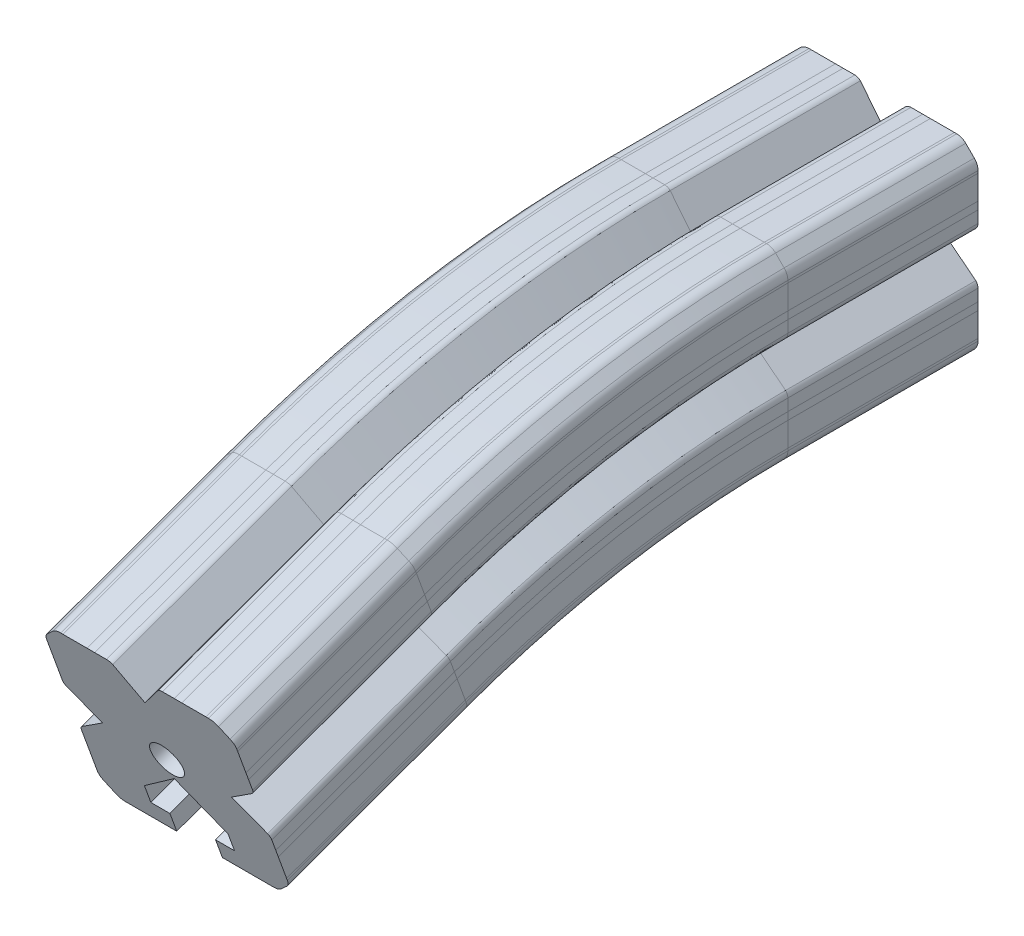
SolidWorks part; units mm, degrees
material "PET"
ref_plane "Front Plane" through (0, 0, 0) normal (0, 0, 1) x (1, 0, 0)
ref_plane "Top Plane" through (0, 0, 0) normal (0, 1, 0) x (1, 0, 0)
ref_plane "Right Plane" through (0, 0, 0) normal (1, 0, 0) x (0, 0, -1)
ref_plane "Plane1" through (0, 0, -304.8) normal (0, 0, -1) x (-1, 0, 0)
sketch "Sketch1" plane through (0, 0, -304.8) normal (0, 0, -1) x (-1, 0, 0)
  line L0 (14.3277, 19.117) -> (9.4982, 19.117)
  line L1 (7.9742, 19.117) -> (5.6176, 19.117)
  line L2 (4.064, 17.5634) -> (4.064, 16.6067) construction
  line L10 (-4.064, 16.6067) -> (-4.064, 17.5634) construction
  line L11 (-5.6176, 19.117) -> (-7.9742, 19.117)
  line L12 (-9.4982, 19.117) -> (-14.3277, 19.117)
  line L13 (-19.05, 14.3948) -> (-19.05, 9.5631)
  line L14 (-19.05, 8.0434) -> (-19.05, 5.6847)
  line L15 (-17.4964, 4.131) -> (-16.5396, 4.131) construction
  line L23 (-16.5396, -3.997) -> (-17.4964, -3.997) construction
  line L24 (-19.05, -5.5506) -> (-19.05, -7.9093)
  line L25 (-19.05, -9.429) -> (-19.05, -14.2607)
  line L26 (-14.3277, -18.983) -> (-9.4961, -18.983)
  line L27 (-7.9763, -18.983) -> (-5.6176, -18.983)
  line L37 (5.6176, -18.983) -> (7.9763, -18.983)
  line L38 (9.4961, -18.983) -> (14.3277, -18.983)
  line L39 (19.05, -14.2607) -> (19.05, -9.429)
  line L40 (19.05, -7.9093) -> (19.05, -5.5506)
  line L41 (17.4964, -3.997) -> (16.5396, -3.997) construction
  line L49 (16.5396, 4.131) -> (17.4964, 4.131) construction
  line L50 (19.05, 5.6847) -> (19.05, 8.0434)
  line L51 (19.05, 9.5631) -> (19.05, 14.3948)
  line L52 (19.05, 5.6847) -> (17.4964, 5.6847) construction
  line L53 (17.4964, 5.6847) -> (17.4964, 4.131) construction
  line L54 (17.4964, 5.6847) -> (18.5065, 4.5043) construction
  line L55 (16.5396, 4.131) -> (12.8784, 0.067) construction
  line L56 (4.064, 16.6067) -> (4.064, 12.9818) construction
  line L57 (4.064, 12.9818) -> (-4.064, 12.9818) construction
  line L58 (-4.064, 12.9818) -> (-4.064, 16.6067) construction
  line L62 (-5.6176, -18.983) -> (5.6176, -18.983)
  line L66 (12.8784, 0.067) -> (16.5396, -3.997) construction
  line L67 (-16.5396, 4.131) -> (-12.8784, 0.067) construction
  line L68 (-12.8784, 0.067) -> (-16.5396, -3.997) construction
  line L69 (-15.8475, 19.117) -> (-14.3277, 19.117)
  line L70 (-9.4982, 19.117) -> (-7.9742, 19.117)
  line L71 (7.9742, 19.117) -> (9.4982, 19.117)
  line L72 (14.3277, 19.117) -> (15.8475, 19.117)
  line L73 (19.05, 15.9145) -> (19.05, 14.3948)
  line L74 (19.05, 9.5631) -> (19.05, 8.0434)
  line L75 (19.05, -7.9093) -> (19.05, -9.429)
  line L76 (19.05, -14.2607) -> (19.05, -15.7805)
  line L77 (15.8475, -18.983) -> (14.3277, -18.983)
  line L78 (9.4961, -18.983) -> (7.9763, -18.983)
  line L79 (-7.9763, -18.983) -> (-9.4961, -18.983)
  line L80 (-14.3277, -18.983) -> (-15.8475, -18.983)
  line L81 (-19.05, -15.7805) -> (-19.05, -14.2607)
  line L82 (-19.05, -9.429) -> (-19.05, -7.9093)
  line L83 (-19.05, 8.0434) -> (-19.05, 9.5631)
  line L84 (-19.05, 14.3948) -> (-19.05, 15.9145)
  line L85 (-15.8475, -18.983) -> (-19.05, -15.7805)
  line L86 (15.8475, -18.983) -> (19.05, -15.7805)
  line L87 (0, 12.9818) -> (4.519, 18.662)
  line L88 (-4.519, 18.662) -> (0, 12.9818)
  line L89 (18.5065, 4.5043) -> (12.8784, 0.067)
  line L90 (12.8784, 0.067) -> (18.595, -4.452)
  line L91 (-18.595, 4.5861) -> (-12.8784, 0.067)
  line L92 (-18.595, -4.452) -> (-12.8784, 0.067)
  line L93 (-19.05, 15.9145) -> (-15.8475, 19.117)
  line L94 (15.8475, 19.117) -> (19.05, 15.9145)
  arc A2 (5.6176, 19.117) -> (4.064, 17.5634) centre (5.6176, 17.5634) ccw construction
  arc A11 (-4.064, 17.5634) -> (-5.6176, 19.117) centre (-5.6176, 17.5634) ccw construction
  arc A14 (-15.8475, 19.117) -> (-19.05, 15.9145) centre (-15.8751, 15.9422) ccw construction
  arc A17 (-19.05, 5.6847) -> (-17.4964, 4.131) centre (-17.4964, 5.6847) ccw construction
  arc A26 (-17.4964, -3.997) -> (-19.05, -5.5506) centre (-17.4964, -5.5506) ccw construction
  arc A29 (-19.05, -15.7805) -> (-15.8475, -18.983) centre (-15.8751, -15.8081) ccw construction
  arc A44 (15.8475, -18.983) -> (19.05, -15.7805) centre (15.8751, -15.8081) ccw construction
  arc A47 (19.05, -5.5506) -> (17.4964, -3.997) centre (17.4964, -5.5506) ccw construction
  arc A56 (17.4964, 4.131) -> (19.05, 5.6847) centre (17.4964, 5.6847) ccw construction
  arc A59 (19.05, 15.9145) -> (15.8475, 19.117) centre (15.8751, 15.9422) ccw construction
  circle A60 centre (0, 0) radius 3.3274 construction
  spline S0 degree 2 poles (-18.595, 4.5861) (-19.0376, 5.0374) (-19.05, 5.6847) knots 0 0 0 1 1 1
  spline S1 degree 2 poles (4.519, 18.662) (4.9741, 19.1064) (5.6176, 19.117) knots 0 0 0 1 1 1
  spline S2 degree 2 poles (-4.519, 18.662) (-4.9741, 19.1064) (-5.6176, 19.117) knots 0 0 0 1 1 1
  spline S3 degree 2 poles (18.5065, 4.5043) (19.0351, 4.9715) (19.05, 5.6847) knots 0 0 0 1 1 1
  spline S4 degree 2 poles (18.595, -4.452) (19.0328, -4.8947) (19.05, -5.5506) knots 0 0 0 1 1 1
  spline S5 degree 2 poles (-18.595, -4.452) (-19.0413, -4.9116) (-19.05, -5.5506) knots 0 0 0 1 1 1
sketch "Sketch2" plane through (0, 0, 0) normal (1, 0, 0) x (0, -1, 0)
  line L1 (0, 266.7) -> (0, 304.8)
  line L2 (12.2545, 197.2015) -> (25.2854, 161.3992)
  arc A1 (0, 266.7) -> (12.2545, 197.2015) centre (203.2, 266.7) ccw
sweep "Sweep4" add profiles "Sketch1" path "Sketch2"
sketch "Sketch12" plane through (0, 0, -304.8) normal (0, 0, -1) x (-1, 0, 0)
  line L0 (-12.8784, 0.067) -> (12.8784, 0.067) construction
  circle A0 centre (0, 0.067) radius 3.3274
extrude "Cut-Extrude3" cut sketch "Sketch12" against normal blind 16.51
sketch "Sketch18" plane through (0, 48.9149, -134.3925) normal (0, -0.342, 0.9397) x (1, 0, 0)
  line L0 (-12.8784, -78.8953) -> (12.8784, -78.8953) construction
  circle A0 centre (0, -78.8953) radius 3.3274
extrude "Cut-Extrude5" cut sketch "Sketch18" against normal blind 16.51
sketch "Sketch20" plane through (0, 0, -304.8) normal (0, 0, -1) x (-1, 0, 0)
  line L0 (0, -18.983) -> (4.572, -18.983) construction
  line L1 (-5.6176, -18.983) -> (5.6176, -18.983) construction
  line L2 (4.572, -18.983) -> (-4.572, -18.983)
  line L3 (-5.6176, -18.983) -> (5.6176, -18.983) construction
  line L4 (-4.572, -18.983) -> (-4.572, -14.9698)
  line L5 (-4.572, -14.9698) -> (-8.382, -14.9698)
  line L6 (-8.382, -14.9698) -> (-8.382, -11.1598)
  line L7 (-8.382, -11.1598) -> (0, -4.1264)
  line L8 (4.572, -18.983) -> (4.572, -14.9698)
  line L9 (4.572, -14.9698) -> (8.382, -14.9698)
  line L10 (8.382, -14.9698) -> (8.382, -11.1598)
  line L11 (8.382, -11.1598) -> (0, -4.1264)
  dimension "D1" = 4.572
  dimension "D2" = 9.144
  dimension "D3" = 4.0132
  dimension "D4" = 4.0132
  dimension "D5" = 3.81
  dimension "D6" = 3.81
  dimension "D7" = 3.81
  dimension "D8" = 3.81
  dimension "D9" = 50
  dimension "D10" = 50
extrude "Cut-Extrude6" cut sketch "Sketch20" against normal blind 38.1 contours L9 L10 L11 L7 L6 L5 L4 L2 L8
sketch "Sketch21" plane through (0, 48.9149, -134.3925) normal (0, -0.342, 0.9397) x (1, 0, 0)
  line L0 (0, -97.9453) -> (4.572, -97.9453) construction
  line L1 (5.6176, -97.9453) -> (-5.6176, -97.9453) construction
  line L2 (4.572, -97.9453) -> (-4.572, -97.9453)
  line L3 (-4.572, -97.9453) -> (-4.572, -93.9321)
  line L4 (-4.572, -93.9321) -> (-8.382, -93.9321)
  line L5 (-8.382, -93.9321) -> (-8.382, -90.1221)
  line L6 (-8.382, -90.1221) -> (0, -83.0887)
  line L7 (4.572, -97.9453) -> (4.572, -93.9321)
  line L8 (4.572, -93.9321) -> (8.382, -93.9321)
  line L9 (8.382, -93.9321) -> (8.382, -90.1221)
  line L10 (8.382, -90.1221) -> (0, -83.0887)
  dimension "D1" = 4.572
  dimension "D2" = 9.144
  dimension "D3" = 4.0132
  dimension "D4" = 3.81
  dimension "D5" = 3.81
  dimension "D6" = 4.0132
  dimension "D7" = 3.81
  dimension "D8" = 3.81
  dimension "D9" = 50
  dimension "D10" = 50
extrude "Cut-Extrude7" cut sketch "Sketch21" against normal blind 38.1
fillet "Fillet1" radius 2.54 24 edges at (-15.8475, 19.117, -285.75) (-15.8475, 15.7395, -228.0951) (-19.05, 15.9145, -285.75) (-19.05, 12.5857, -228.6512) (-19.05, -15.7805, -285.75) (-19.05, -18.6278, -234.1549) (-15.8475, -18.983, -285.75) (-15.8475, -21.7816, -234.711) (15.8475, -18.983, -285.75) (15.8475, -21.7816, -234.711) (19.05, -15.7805, -285.75) (19.05, -18.6278, -234.1549) (19.05, 15.9145, -285.75) (19.05, 12.5857, -228.6512) (15.8475, 19.117, -285.75) (15.8475, 15.7395, -228.0951) (-15.8475, -0.8058, -172.762) (-19.05, -3.8152, -173.8573) (-19.05, -33.5987, -184.6976) (-15.8475, -36.6081, -185.7929) (15.8475, -36.6081, -185.7929) (19.05, -33.5987, -184.6976) (19.05, -3.8152, -173.8573) (15.8475, -0.8058, -172.762)
